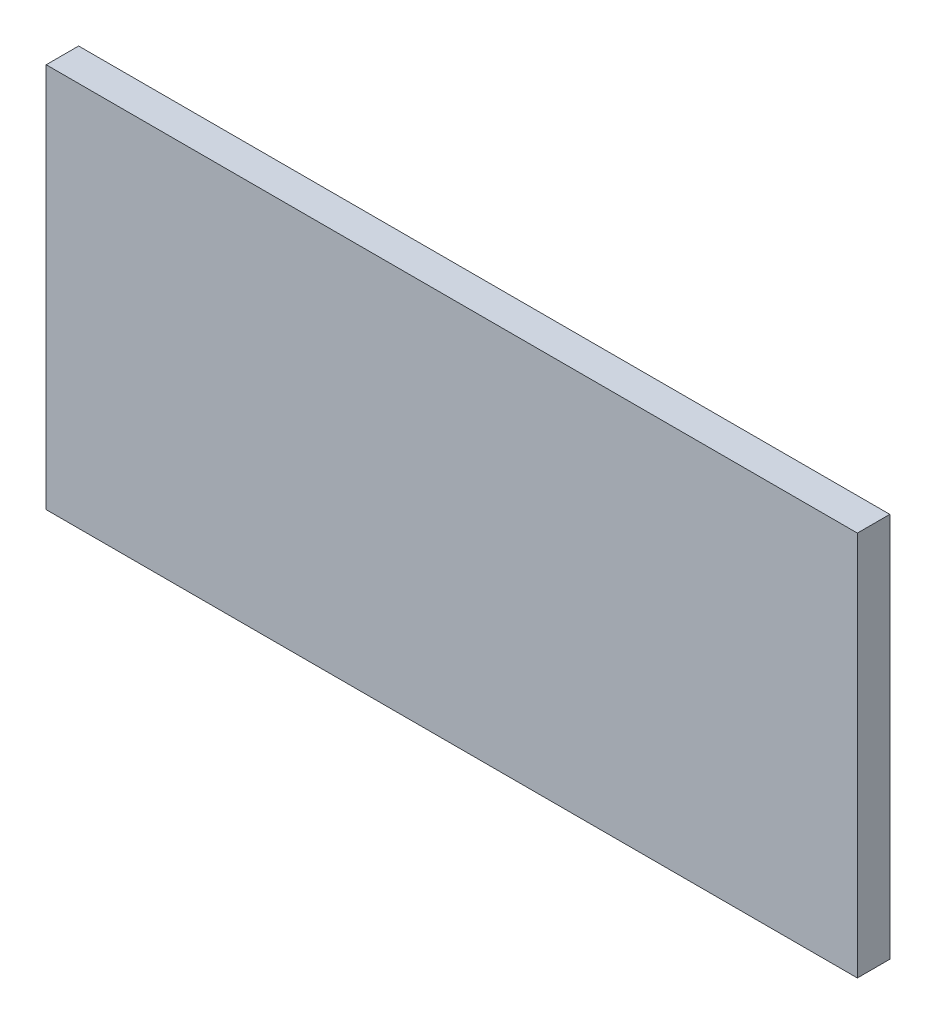
SolidWorks part; units mm, degrees
ref_plane "前视基准面" through (0, 0, 0) normal (0, 0, 1) x (1, 0, 0)
ref_plane "上视基准面" through (0, 0, 0) normal (0, 1, 0) x (1, 0, 0)
ref_plane "右视基准面" through (0, 0, 0) normal (1, 0, 0) x (0, 0, -1)
other "Configuration Table"
sketch "草图1" plane through (0, 0, 0) normal (0, 0, 1) x (1, 0, 0)
  line L0 (0, 0) -> (40, 0)
  line L1 (40, 0) -> (40, 19)
  line L2 (40, 19) -> (0, 19)
  line L3 (0, 19) -> (0, 0)
  dimension "width" = 40
  dimension "height" = 19
extrude "BlockExtrude" add sketch "草图1" along normal blind 1.6
